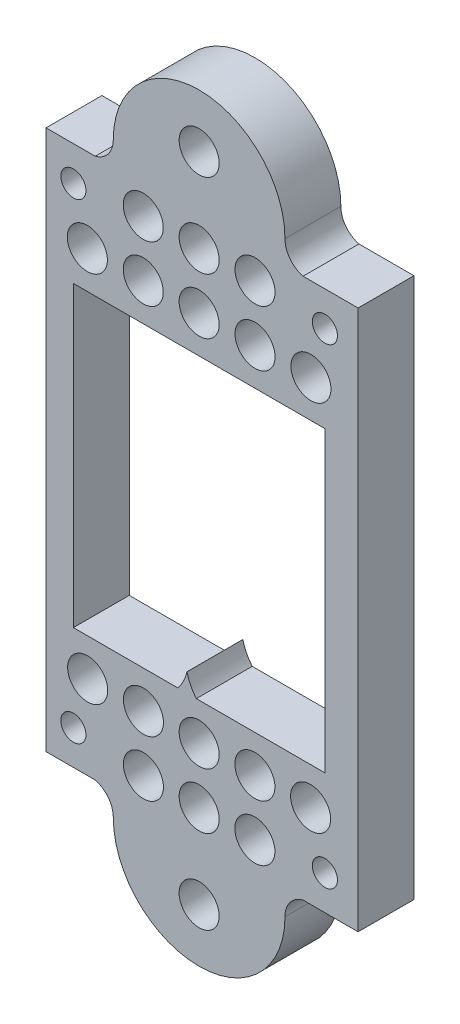
SolidWorks part; units mm, degrees
ref_plane "Front Plane" through (0, 0, 0) normal (0, 0, 1) x (1, 0, 0)
ref_plane "Top Plane" through (0, 0, 0) normal (0, 1, 0) x (1, 0, 0)
ref_plane "Right Plane" through (0, 0, 0) normal (1, 0, 0) x (0, 0, -1)
sketch "Sketch1" plane through (0, 0, 0) normal (0, 0, 1) x (1, 0, 0)
  line L0 (-13.5, -10.2592) -> (-1.3, -10.2592) construction
  line L1 (-16.4365, 29) -> (-11.1559, 29)
  line L2 (-16.4365, 29) -> (-16.4365, -29)
  line L3 (-16.4365, -29) -> (-11.1559, -29)
  line L4 (17.0635, 29) -> (17.0635, -29)
  line L5 (-13.5, 16) -> (13.5, 16)
  line L6 (-13.5, 16) -> (-13.5, -16)
  line L7 (-13.5, -16) -> (-2.3, -16)
  line L8 (13.5, 16) -> (13.5, -16)
  line L9 (-1.3, -10.2592) -> (-1.3, -16) construction
  line L10 (-2.3, -16) -> (-0.3, -16) construction
  line L12 (-0.3, -16) -> (13.5, -16)
  line L14 (-19.5, 29.3) -> (19.5, 29.3) construction
  line L15 (-19.5, 29.3) -> (-19.5, -29.3) construction
  line L16 (-19.5, -29.3) -> (19.5, -29.3) construction
  line L17 (19.5, 29.3) -> (19.5, -29.3) construction
  line L19 (-5, 27.5542) -> (5, 27.5542) construction
  line L20 (0, 0) -> (4.3335, 0) construction
  line L21 (11.1559, 29) -> (17.0635, 29)
  line L22 (11.1559, -29) -> (17.0635, -29)
  line L23 (0, 35) -> (0, 28.0589) construction
  circle A2 centre (-13.5, 25.3) radius 1.35
  circle A4 centre (13.5, -25.3) radius 1.35
  circle A5 centre (-13.5, -25.3) radius 1.35
  circle A6 centre (13.5, 25.3) radius 1.35
  arc A7 (-9.2149, 31.5247) -> (9.2149, 31.5247) centre (0, 31.5247) cw
  circle A8 centre (0, 35) radius 2.15
  circle A13 centre (0, -35) radius 2.15
  arc A16 (-9.2149, 31.5247) -> (-11.1559, 29) centre (-11.7911, 31.4968) cw
  arc A17 (9.2149, 31.5247) -> (11.1559, 29) centre (11.7911, 31.4968) ccw
  arc A21 (9.2149, -31.5247) -> (11.1559, -29) centre (11.7911, -31.4968) cw
  arc A22 (-9.2149, -31.5247) -> (-11.1559, -29) centre (-11.7911, -31.4968) ccw
  arc A23 (-9.2149, -31.5247) -> (9.2149, -31.5247) centre (0, -31.5247) ccw
  arc A24 (-2.3, -16) -> (-1.3, -14) centre (-5.8378, -12.9811) ccw
  arc A25 (-0.3, -16) -> (-1.3, -14) centre (3.2378, -12.9811) cw
  point P10 (-16.4365, 0)
  point P11 (0, 16)
  point P12 (-13.5, 0)
  point P16 (-1.3, -16)
  point P22 (0, 0)
  point P23 (-7.8543, 29)
  point P24 (-11.5262, 29)
  point P25 (0, 35)
  point P29 (19.5, 0)
  point P30 (0, 29.3)
  point P46 (0, 27.5542)
  dimension "D8" = 2.7
  dimension "D22" = 4.3
  dimension "D23" = 6
  dimension "D1" = 27
  dimension "D2" = 33.5
  dimension "D3" = 58
  dimension "D4" = 32
  dimension "D5" = 12.2
  dimension "D6" = 2
  dimension "D9" = 58.6
  dimension "D10" = 39
  dimension "D11" = 6
  dimension "D12" = 4
  dimension "D13" = 4
  dimension "D14" = 6
  dimension "D15" = 6
  dimension "D16" = 6
  dimension "D17" = 4
  dimension "D18" = 4
  dimension "D21" = 10
  dimension "D24" = 2
extrude "Boss-Extrude1" add sketch "Sketch1" along normal blind 6
sketch "Sketch2" plane through (0, 0, 6) normal (0, 0, 1) x (1, 0, 0)
  line L2 (-13.5, -16) -> (-2.3, -16) construction
  line L3 (13.5, 16) -> (-13.5, 16) construction
  circle A0 centre (-12, 20) radius 2.15
  circle A1 centre (-6, 20) radius 2.15
  circle A2 centre (0, 20) radius 2.15
  circle A3 centre (6, 20) radius 2.15
  circle A4 centre (12, 20) radius 2.15
  circle A5 centre (-6, 26) radius 2.15
  circle A6 centre (0, 26) radius 2.15
  circle A7 centre (6, 26) radius 2.15
  circle A8 centre (-11.9673, -20) radius 2.15
  circle A9 centre (-5.9837, -20) radius 2.15
  circle A10 centre (0, -20) radius 2.15
  circle A11 centre (5.9837, -20) radius 2.15
  circle A12 centre (11.9673, -20) radius 2.15
  circle A13 centre (-5.9837, -26) radius 2.15
  circle A14 centre (0, -26) radius 2.15
  circle A15 centre (5.9837, -26) radius 2.15
  dimension "D1" = 4.3
  dimension "D5" = 4.3
  dimension "D11" = 4.3
  dimension "D12" = 4.3
  dimension "D13" = 4.3
  dimension "D14" = 4.3
  dimension "D15" = 4.3
  dimension "D16" = 4.3
  dimension "D2" = 4
  dimension "D3" = 4
  dimension "D6" = 6
  dimension "D10" = 6
  dimension "D4" = 5
  dimension "D9" = 5
extrude "Cut-Extrude1" cut sketch "Sketch2" against normal blind 4.2
